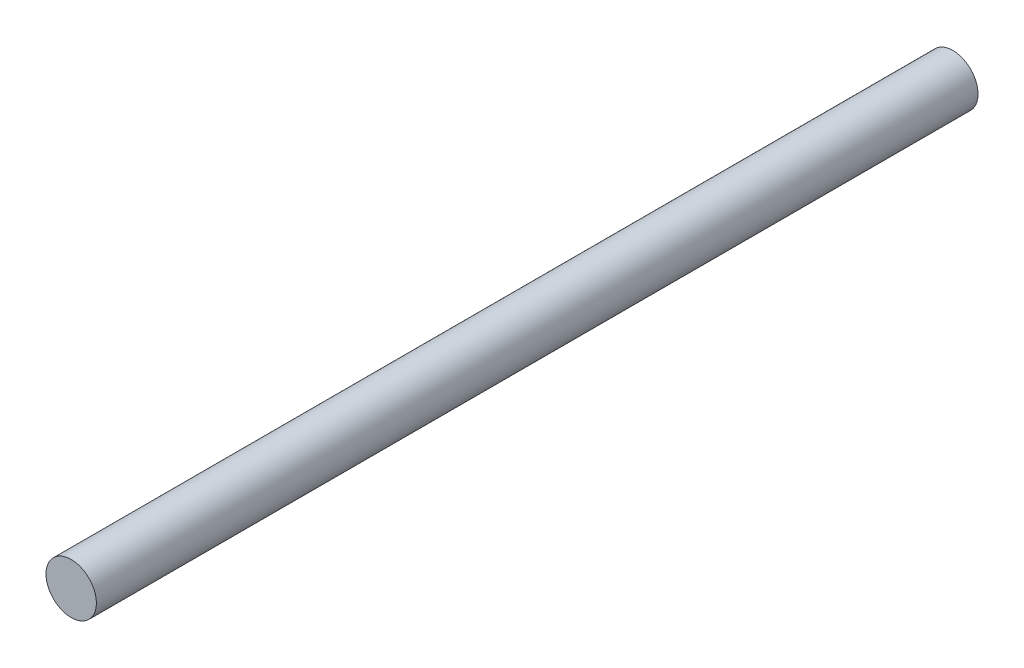
SolidWorks part; units mm, degrees
ref_plane "Front Plane" through (0, 0, 0) normal (0, 0, 1) x (1, 0, 0)
ref_plane "Top Plane" through (0, 0, 0) normal (0, 1, 0) x (1, 0, 0)
ref_plane "Right Plane" through (0, 0, 0) normal (1, 0, 0) x (0, 0, -1)
sketch "Sketch1" plane through (0, 0, 0) normal (0, 0, 1) x (1, 0, 0)
  circle A0 centre (0, 0) radius 4.8
  dimension "D1" = 9.6
extrude "Boss-Extrude1" add sketch "Sketch1" along normal mid plane 168
